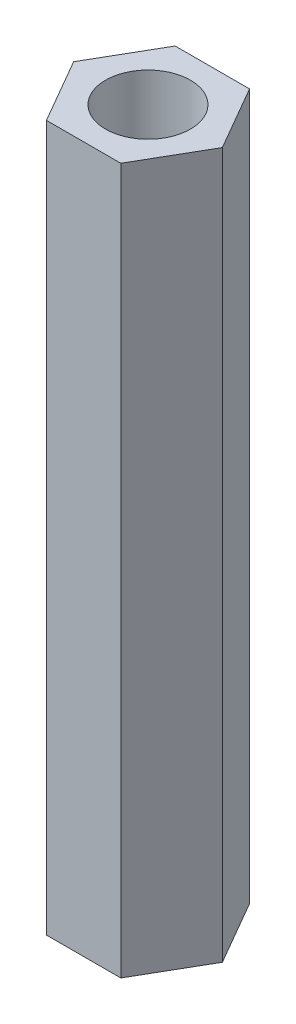
SolidWorks part; units mm, degrees
ref_plane "Front Plane" through (0, 0, 0) normal (0, 0, 1) x (1, 0, 0)
ref_plane "Top Plane" through (0, 0, 0) normal (0, 1, 0) x (1, 0, 0)
ref_plane "Right Plane" through (0, 0, 0) normal (1, 0, 0) x (0, 0, -1)
sketch "Sketch1" plane through (0, 0, 0) normal (0, 1, 0) x (1, 0, 0)
  line L1 (-3.3717, 0) -> (-1.6859, -2.92)
  line L2 (-1.6859, -2.92) -> (1.6859, -2.92)
  line L3 (1.6859, -2.92) -> (3.3717, 0)
  line L4 (3.3717, 0) -> (1.6859, 2.92)
  line L5 (1.6859, 2.92) -> (-1.6859, 2.92)
  line L6 (-1.6859, 2.92) -> (-3.3717, 0)
  circle A0 centre (0, 0) radius 2.92 construction
  circle A1 centre (0, 0) radius 1.925
  dimension "D1" = 5.84
  dimension "D2" = 3.85
extrude "Boss-Extrude1" add sketch "Sketch1" along normal blind 32
